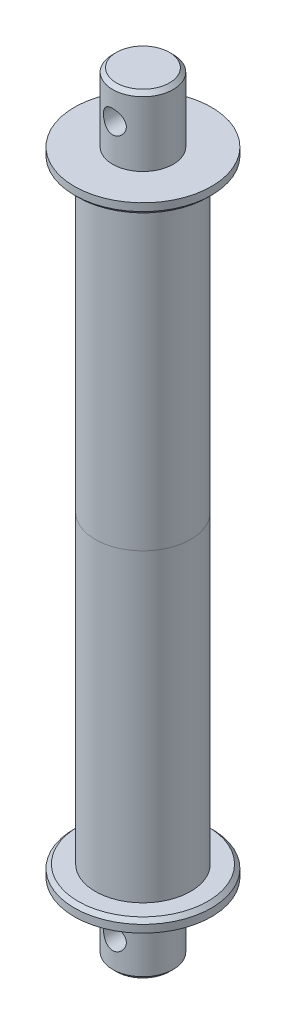
SolidWorks part; units mm, degrees
material "普通碳钢"
ref_plane "前视基准面" through (0, 0, 0) normal (0, 0, 1) x (1, 0, 0)
ref_plane "上视基准面" through (0, 0, 0) normal (0, 1, 0) x (1, 0, 0)
ref_plane "右视基准面" through (0, 0, 0) normal (1, 0, 0) x (0, 0, -1)
sketch "草图1" plane through (0, 0, 0) normal (0, 1, 0) x (1, 0, 0)
  circle A0 centre (0, 0) radius 7.95
  dimension "D1" = 15.9
extrude "凸台-拉伸1" add sketch "草图1" along normal blind 18 contours A0
chamfer "倒角2" distance 1 angle 45 1 edges at (0, 18, 7.95)
sketch "草图9" plane through (0, 0, 0) normal (0, 0, 1) x (1, 0, 0)
  line L0 (0, -19.8) -> (0, 19.8) construction
  line L1 (19.8, 0) -> (-19.8, 0) construction
  circle A0 centre (0, 9.7) radius 3
  dimension "D1" = 9.7
  dimension "D2" = 6
extrude "切除-拉伸2" cut sketch "草图9" against normal through all both and the other way through all
sketch "草图4" plane through (0, 0, 0) normal (0, 1, 0) x (1, 0, 0)
  circle A0 centre (0, 0) radius 18
extrude "凸台-拉伸2" add sketch "草图4" against normal blind 3
chamfer "倒角1" distance 1 angle 45 1 edges at (0, -3, 18)
ref_plane "基准面4" through (0, -3, 0) normal (0, -1, 0) x (-1, 0, 0)
sketch "草图5" plane through (0, -3, 0) normal (0, -1, 0) x (-1, 0, 0)
  circle A0 centre (0, 0) radius 12.5
extrude "凸台-拉伸3" add sketch "草图5" along normal blind 80
ref_plane "基准面5" through (0, -83, 0) normal (0, -1, 0) x (-1, 0, 0)
mirror "镜向3" about plane through (0, -83, 0) normal (0, -1, 0) of bodies 103 108
